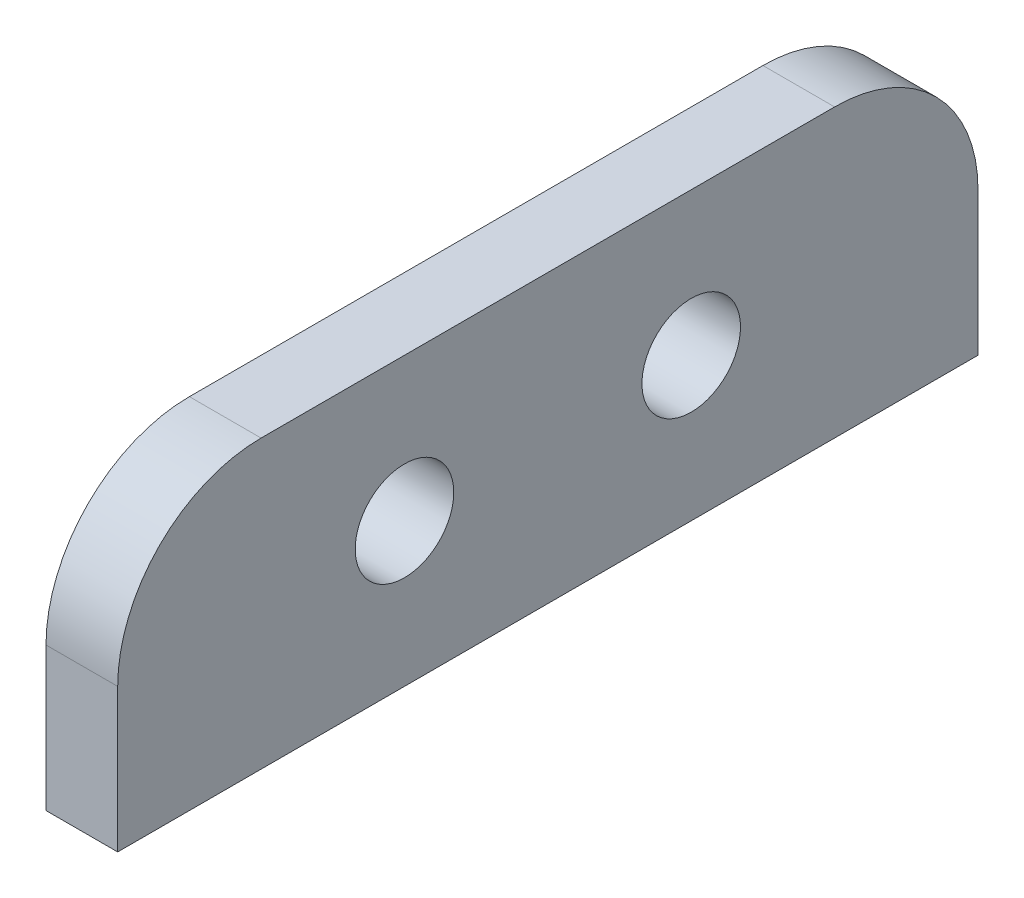
SolidWorks part; units mm, degrees
ref_plane "Front Plane" through (0, 0, 0) normal (0, 0, 1) x (1, 0, 0)
ref_plane "Top Plane" through (0, 0, 0) normal (0, 1, 0) x (1, 0, 0)
ref_plane "Right Plane" through (0, 0, 0) normal (1, 0, 0) x (0, 0, -1)
sketch "Sketch1" plane through (0, 0, 0) normal (1, 0, 0) x (0, 0, -1)
  line L0 (-8, 0) -> (8, 0) construction
  line L1 (24, -8) -> (-24, -8)
  line L2 (24, -8) -> (24, 8)
  line L3 (24, 8) -> (-24, 8)
  line L4 (-24, -8) -> (-24, 8)
  line L5 (24, -8) -> (-24, 8) construction
  line L6 (24, 8) -> (-24, -8) construction
  line L7 (8, 0) -> (8, -8) construction
  circle A0 centre (-8, 0) radius 2.75
  circle A1 centre (8, 0) radius 2.75
  point P0 (0, 0)
  dimension "D5" = 5.5
  dimension "D1" = 48
  dimension "D2" = 16
  dimension "D4" = 16
extrude "Boss-Extrude1" add sketch "Sketch1" along normal blind 4
fillet "Fillet1" radius 8 2 edges at (2, 8, 24) (2, 8, -24)
